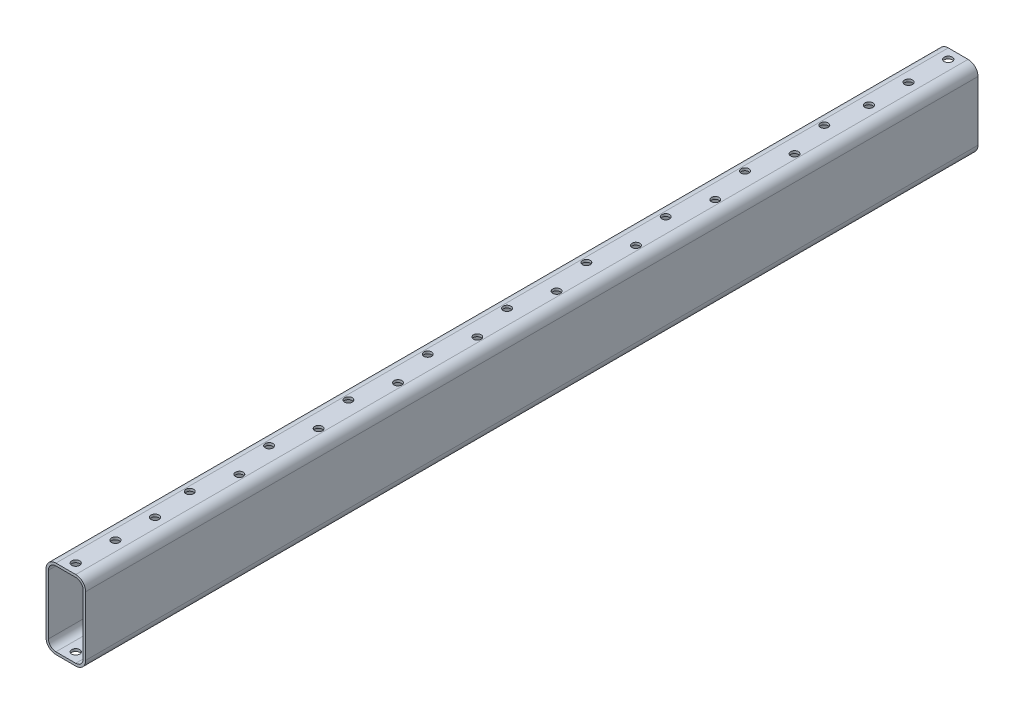
SolidWorks part; units mm, degrees
material "6061-T6 (SS)"
ref_plane "Front Plane" through (0, 0, 0) normal (0, 0, 1) x (1, 0, 0)
ref_plane "Top Plane" through (0, 0, 0) normal (0, 1, 0) x (1, 0, 0)
ref_plane "Right Plane" through (0, 0, 0) normal (1, 0, 0) x (0, 0, -1)
sketch "Sketch1" plane through (0, 0, 0) normal (0, 0, 1) x (1, 0, 0)
  line L1 (-6.35, -25.4) -> (6.35, -25.4)
  line L2 (-12.7, -19.05) -> (-12.7, 19.05)
  line L3 (-6.35, 25.4) -> (6.35, 25.4)
  line L4 (12.7, -19.05) -> (12.7, 19.05)
  line L5 (-12.7, -25.4) -> (12.7, 25.4) construction
  line L6 (-12.7, 25.4) -> (12.7, -25.4) construction
  arc A0 (-12.7, -19.05) -> (-6.35, -25.4) centre (-6.35, -19.05) ccw
  arc A1 (6.35, -25.4) -> (12.7, -19.05) centre (6.35, -19.05) ccw
  arc A2 (6.35, 25.4) -> (12.7, 19.05) centre (6.35, 19.05) cw
  arc A3 (-12.7, 19.05) -> (-6.35, 25.4) centre (-6.35, 19.05) cw
  point P0 (0, 0)
  dimension "D3" = 6.35
  dimension "D1" = 50.8
  dimension "D2" = 25.4
extrude "Extrude-Thin1" add sketch "Sketch1" along normal blind 571.5 thin thin type one direction reverse wall 1.5875
hole_wizard "#10 Clearance Hole1" positions "3DSketch1" profile "Sketch3" hole size "#10" standard "ANSI Inch" end condition through all
sketch3d "3DSketch1"
  line L1 (6.35, 25.4, 0) -> (-6.35, 25.4, 0) construction
  line L6 (0, 25.4, 571.5) -> (0, 25.4, 0) construction
  line L7 (6.35, 25.4, 571.5) -> (-6.35, 25.4, 571.5) construction
  point P57 (0, 25.4, 6.35)
  point P59 (0, 25.4, 31.75)
  point P61 (0, 25.4, 57.15)
  point P63 (0, 25.4, 539.75)
  point P65 (0, 25.4, 514.35)
  point P67 (0, 25.4, 565.15)
  dimension "D1" = 25.4
  dimension "D2" = 25.4
  dimension "D3" = 6.35
  dimension "D4" = 25.4
  dimension "D5" = 25.4
  dimension "D6" = 6.35
sketch "Sketch3" plane through (0, 25.4, 565.15) normal (1, 0, 0) x (0, 0, 1)
  line L0 (0, 0) -> (0, 50.8)
  line L1 (0, 50.8) -> (2.5527, 50.8)
  line L2 (2.5527, 50.8) -> (2.5527, 0)
  line L5 (2.5527, 0) -> (0, 0)
  line L11 (0, -6.35) -> (0, 107.95) construction
  dimension "Thru Hole Dia." = 5.1054
  dimension "Thru Hole Depth" = 50.8
hole_wizard "3/16 (0.195) Diameter Hole1" positions "Sketch4" profile "Sketch5" hole size "3/16" standard "ANSI Inch"
sketch "Sketch4" plane through (0, 25.4, 0) normal (0, 1, 0) x (1, 0, 0)
  point P145 (-3.175, -82.55)
  point P148 (3.175, -107.95)
  point P151 (-3.175, -133.35)
  point P154 (3.175, -158.75)
  point P157 (-3.175, -184.15)
  point P160 (3.175, -209.55)
  point P163 (-3.175, -234.95)
  point P166 (3.175, -260.35)
  point P169 (-3.175, -285.75)
  point P172 (3.175, -311.15)
  point P175 (-3.175, -336.55)
  point P178 (3.175, -361.95)
  point P181 (-3.175, -387.35)
  point P184 (3.175, -412.75)
  point P187 (-3.175, -438.15)
  point P190 (3.175, -463.55)
  point P193 (-3.175, -488.95)
sketch "Sketch5" plane through (-3.175, 25.4, 82.55) normal (1, 0, 0) x (0, 0, 1)
  line L0 (0, 0) -> (0, 1.5875)
  line L1 (0, 1.5875) -> (2.4765, 1.5875)
  line L2 (2.4765, 1.5875) -> (2.4765, 0)
  line L5 (2.4765, 0) -> (0, 0)
  line L11 (0, -6.35) -> (0, 107.95) construction
  dimension "Thru Hole Dia." = 4.953
  dimension "Thru Hole Depth" = 1.5875
